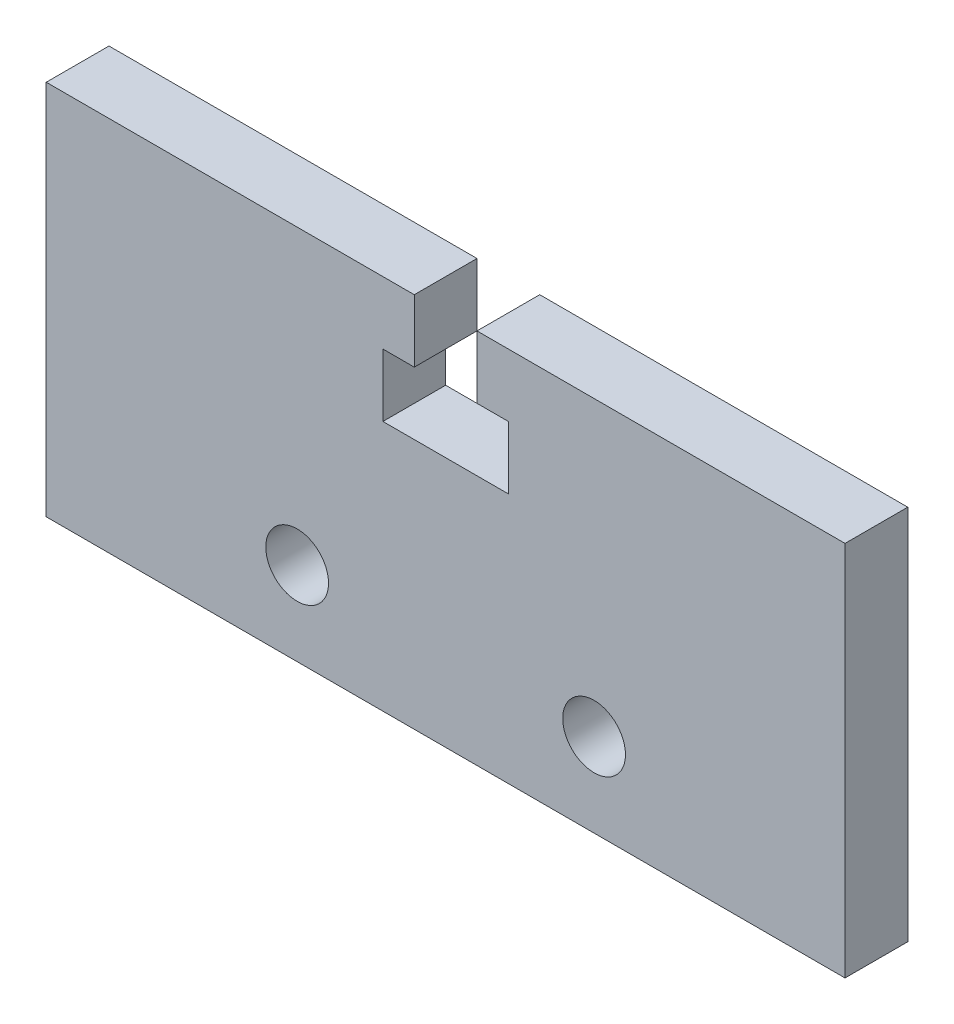
SolidWorks part; units mm, degrees
ref_plane "Alzado" through (0, 0, 0) normal (0, 0, 1) x (1, 0, 0)
ref_plane "Planta" through (0, 0, 0) normal (0, 1, 0) x (1, 0, 0)
ref_plane "Vista lateral" through (0, 0, 0) normal (1, 0, 0) x (0, 0, -1)
sketch "Croquis1" plane through (0, 0, 0) normal (0, 0, 1) x (1, 0, 0)
  line L0 (0, 9) -> (0, 3) construction
  line L1 (19.1, -9) -> (-19.1, -9)
  line L2 (19.1, -9) -> (19.1, 9)
  line L3 (19.1, 9) -> (1.5, 9)
  line L4 (-19.1, -9) -> (-19.1, 9)
  line L5 (19.1, -9) -> (-19.1, 9) construction
  line L6 (19.1, 9) -> (-19.1, -9) construction
  line L7 (3, 3) -> (-3, 3)
  line L8 (-3, 3) -> (-3, 6)
  line L9 (-3, 6) -> (-1.5, 6)
  line L10 (-1.5, 6) -> (-1.5, 9)
  line L11 (1.5, 6) -> (1.5, 9)
  line L12 (3, 6) -> (1.5, 6)
  line L13 (3, 3) -> (3, 6)
  line L14 (-1.5, 9) -> (-19.1, 9)
  circle A0 centre (7.1, -5) radius 1.5
  circle A2 centre (-7.1, -5) radius 1.5
  point P0 (0, 0)
  dimension "D7" = 3
  dimension "D1" = 38.2
  dimension "D2" = 18
  dimension "D3" = 6
  dimension "D4" = 1.5
  dimension "D5" = 3
  dimension "D6" = 3
  dimension "D8" = 4
  dimension "D9" = 12
extrude "Saliente-Extruir1" add sketch "Croquis1" along normal blind 3
